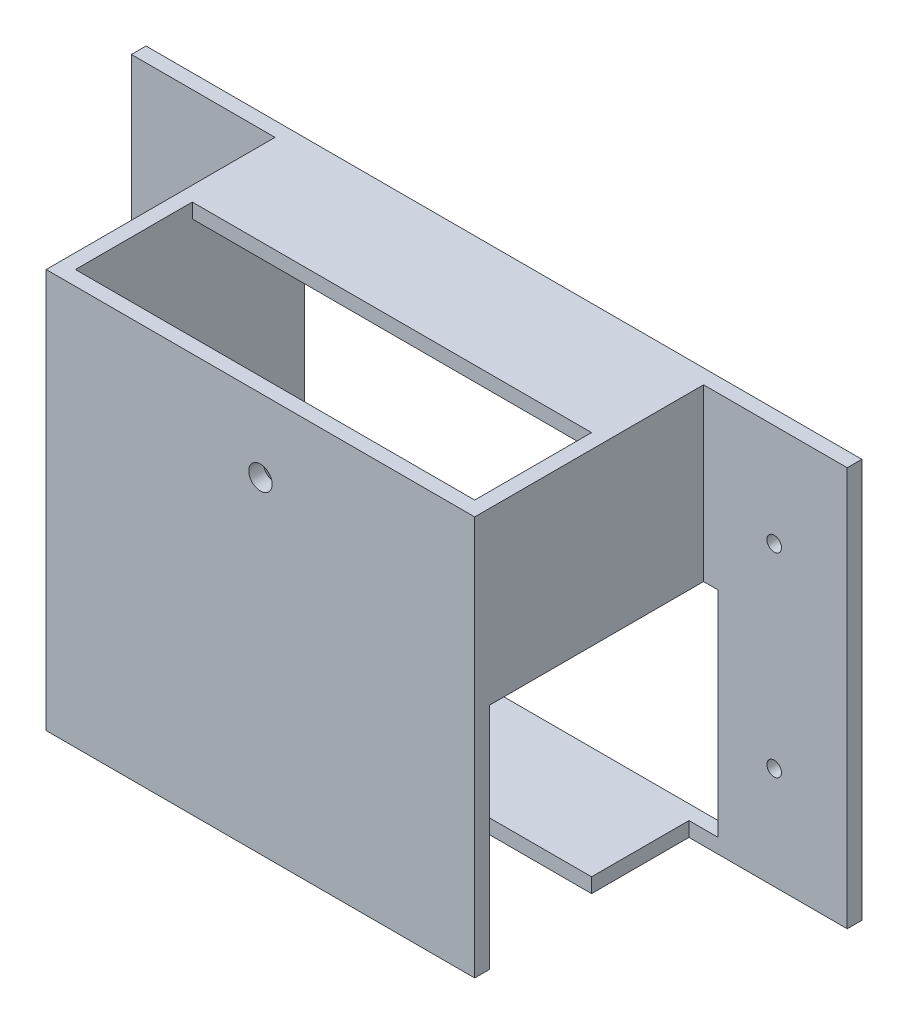
SolidWorks part; units mm, degrees
material "自定义塑料"
ref_plane "前视基准面" through (0, 0, 0) normal (0, 0, 1) x (1, 0, 0)
ref_plane "上视基准面" through (0, 0, 0) normal (0, 1, 0) x (1, 0, 0)
ref_plane "右视基准面" through (0, 0, 0) normal (1, 0, 0) x (0, 0, -1)
sketch "草图1" plane through (0, 0, 0) normal (0, 0, 1) x (1, 0, 0)
  line L1 (-78.4601, 39.0046) -> (68.5399, 39.0046)
  line L2 (-78.4601, 39.0046) -> (-78.4601, -42.9954)
  line L3 (-78.4601, -42.9954) -> (68.5399, -42.9954)
  line L4 (68.5399, 39.0046) -> (68.5399, -42.9954)
  dimension "D1" = 147
  dimension "D2" = 82
extrude "凸台-拉伸1" add sketch "草图1" along normal blind 50
sketch "草图2" plane through (0, 0, 50) normal (0, 0, 1) x (1, 0, 0)
  line L0 (-78.4601, -42.9954) -> (68.5399, -42.9954) construction
  line L1 (-78.4601, 39.0046) -> (-48.9601, 39.0046)
  line L2 (-78.4601, 39.0046) -> (-78.4601, -42.9954)
  line L3 (-78.4601, -42.9954) -> (-48.9601, -42.9954)
  line L4 (-48.9601, 39.0046) -> (-48.9601, -42.9954)
  dimension "D1" = 29.5
extrude "切除-拉伸1" cut sketch "草图2" against normal blind 47
sketch "草图3" plane through (0, 0, 50) normal (0, 0, 1) x (1, 0, 0)
  line L0 (68.5399, 39.0046) -> (-48.9601, 39.0046) construction
  line L1 (68.5399, -42.9954) -> (39.0399, -42.9954)
  line L2 (68.5399, -42.9954) -> (68.5399, 39.0046)
  line L3 (68.5399, 39.0046) -> (39.0399, 39.0046)
  line L4 (39.0399, -42.9954) -> (39.0399, 39.0046)
  dimension "D1" = 29.5
extrude "切除-拉伸2" cut sketch "草图3" against normal blind 47
sketch "草图5" plane through (0, 0, 0) normal (0, 0, -1) x (-1, 0, 0)
  line L0 (-68.5399, 39.0046) -> (78.4601, 39.0046) construction
  line L1 (45.9601, -39.9954) -> (-36.0399, -39.9954)
  line L2 (45.9601, -39.9954) -> (45.9601, 36.0046)
  line L3 (45.9601, 36.0046) -> (-36.0399, 36.0046)
  line L4 (-36.0399, -39.9954) -> (-36.0399, 36.0046)
  line L5 (-68.5399, -42.9954) -> (-68.5399, 39.0046) construction
  dimension "D1" = 82
  dimension "D2" = 76
  dimension "D3" = 3
  dimension "D4" = 32.5
extrude "切除-拉伸3" cut sketch "草图5" against normal blind 47
sketch "草图6" plane through (0, 0, 50) normal (0, 0, 1) x (1, 0, 0)
  line L0 (-48.9601, -42.9954) -> (-48.9601, 39.0046) construction
  line L1 (39.0399, 39.0046) -> (-48.9601, 39.0046) construction
  circle A0 centre (-4.9601, 24.0046) radius 2.4
  dimension "D1" = 4.8
  dimension "D2" = 44
  dimension "D3" = 15
extrude "切除-拉伸4" cut sketch "草图6" against normal blind 4
sketch "草图7" plane through (0, 39.0046, 0) normal (0, 1, 0) x (1, 0, 0)
  line L0 (-48.9601, -3) -> (-48.9601, -50) construction
  line L1 (36.0399, -47) -> (-45.9601, -47)
  line L2 (36.0399, -47) -> (36.0399, -23)
  line L3 (36.0399, -23) -> (-45.9601, -23)
  line L4 (-45.9601, -47) -> (-45.9601, -23)
  line L5 (39.0399, -50) -> (-48.9601, -50) construction
  line L6 (68.5399, 0) -> (-78.4601, 0) construction
  dimension "D1" = 82
  dimension "D2" = 3
  dimension "D3" = 3
  dimension "D4" = 23
extrude "切除-拉伸5" cut sketch "草图7" against normal blind 84
sketch "草图9" plane through (39.0399, 0, 0) normal (1, 0, 0) x (0, 0, -1)
  line L0 (-50, 39.0046) -> (-50, -42.9954) construction
  line L1 (-47, -42.9954) -> (-3, -42.9954)
  line L2 (-47, -42.9954) -> (-47, 4.0046)
  line L3 (-47, 4.0046) -> (-3, 4.0046)
  line L4 (-3, -42.9954) -> (-3, 4.0046)
  line L5 (-3, 39.0046) -> (-50, 39.0046) construction
  line L6 (-3, -42.9954) -> (-50, -42.9954) construction
  line L7 (-3, 39.0046) -> (-3, -42.9954) construction
  dimension "D1" = 3
  dimension "D2" = 35
  dimension "D3" = 0
  dimension "D4" = 0
extrude "切除-拉伸6" cut sketch "草图9" against normal blind 3
sketch "草图10" plane through (0, 0, 3) normal (0, 0, 1) x (1, 0, 0)
  line L1 (36.0399, 4.0046) -> (42.0399, 4.0046)
  line L2 (36.0399, 4.0046) -> (36.0399, -39.9954)
  line L3 (36.0399, -39.9954) -> (42.0399, -39.9954)
  line L4 (42.0399, 4.0046) -> (42.0399, -39.9954)
  dimension "D1" = 6
extrude "切除-拉伸7" cut sketch "草图10" against normal blind 7
sketch "草图12" plane through (0, 0, 0) normal (0, 0, -1) x (-1, 0, 0)
  line L0 (78.4601, 39.0046) -> (78.4601, -42.9954) construction
  line L1 (78.4601, -42.9954) -> (-68.5399, -42.9954) construction
  line L2 (-68.5399, -42.9954) -> (-68.5399, 39.0046) construction
  circle A0 centre (63.4601, 18.0046) radius 1.5
  circle A1 centre (63.4601, -21.9954) radius 1.5
  circle A2 centre (-53.5399, 18.0046) radius 1.5
  circle A3 centre (-53.5399, -21.9954) radius 1.5
  dimension "D1" = 3
  dimension "D2" = 3
  dimension "D6" = 3
  dimension "D7" = 3
  dimension "D3" = 40
  dimension "D4" = 15
  dimension "D5" = 21
  dimension "D8" = 21
  dimension "D9" = 40
  dimension "D10" = 15
  dimension "D11" = 15
extrude "切除-拉伸8" cut sketch "草图12" against normal blind 3
